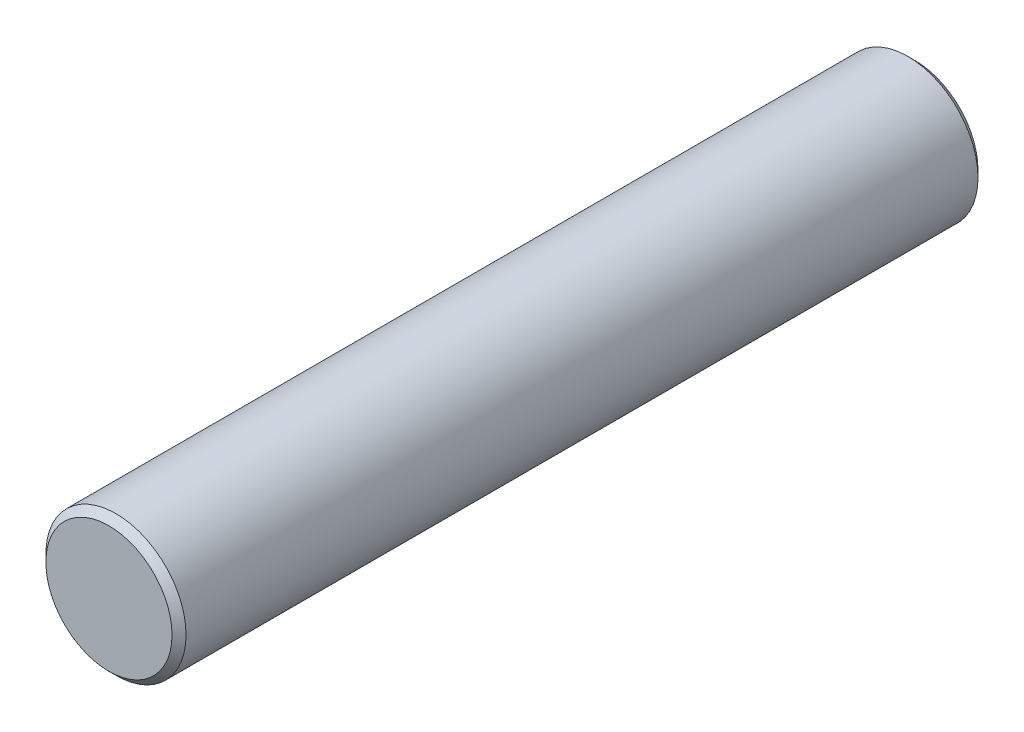
SolidWorks part; units mm, degrees
ref_plane "前视基准面" through (0, 0, 0) normal (0, 0, 1) x (1, 0, 0)
ref_plane "上视基准面" through (0, 0, 0) normal (0, 1, 0) x (1, 0, 0)
ref_plane "右视基准面" through (0, 0, 0) normal (1, 0, 0) x (0, 0, -1)
sketch "草图1" plane through (0, 0, 0) normal (0, 0, 1) x (1, 0, 0)
  circle A0 centre (0, 0) radius 2
  dimension "D1" = 4
extrude "凸台-拉伸1" add sketch "草图1" along normal blind 23
chamfer "倒角1" distance 0.2 angle 45 2 edges at (2, 0, 0) (2, 0, 23)
